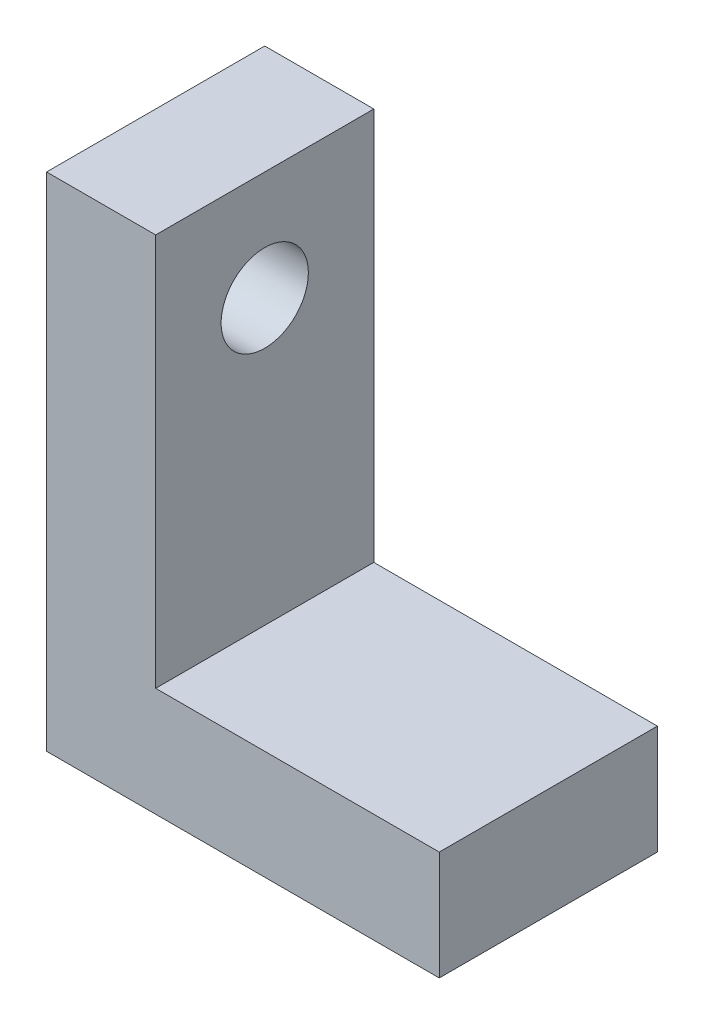
SolidWorks part; units mm, degrees
ref_plane "Alzado" through (0, 0, 0) normal (0, 0, 1) x (1, 0, 0)
ref_plane "Planta" through (0, 0, 0) normal (0, 1, 0) x (1, 0, 0)
ref_plane "Vista lateral" through (0, 0, 0) normal (1, 0, 0) x (0, 0, -1)
sketch "Croquis1" plane through (0, 0, 0) normal (0, 0, 1) x (1, 0, 0)
  line L0 (0, 0) -> (0, 23)
  line L1 (0, 23) -> (5, 23)
  line L2 (5, 23) -> (5, 5)
  line L3 (5, 5) -> (18, 5)
  line L4 (18, 5) -> (18, 0)
  line L5 (18, 0) -> (0, 0)
  dimension "D1" = 23
  dimension "D2" = 5
  dimension "D3" = 5
  dimension "D4" = 18
extrude "Saliente-Extruir1" add sketch "Croquis1" along normal mid plane 10
sketch "Croquis2" plane through (5, 0, 0) normal (1, 0, 0) x (0, 0, -1)
  line L0 (-5, 23) -> (5, 23) construction
  circle A0 centre (0, 18) radius 2
  dimension "D2" = 4
  dimension "D1" = 5
extrude "Cortar-Extruir1" cut sketch "Croquis2" against normal through all
